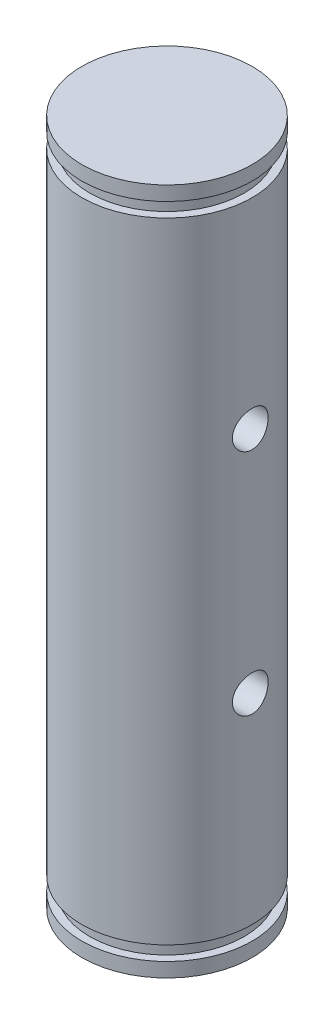
SolidWorks part; units mm, degrees
material "延性铁"
ref_plane "前视基准面" through (0, 0, 0) normal (0, 0, 1) x (1, 0, 0)
ref_plane "上视基准面" through (0, 0, 0) normal (0, 1, 0) x (1, 0, 0)
ref_plane "右视基准面" through (0, 0, 0) normal (1, 0, 0) x (0, 0, -1)
sketch "草图1" plane through (0, 0, 0) normal (0, 1, 0) x (1, 0, 0)
  circle A0 centre (5.9, 0) radius 5.95
  dimension "D1" = 11.9
extrude "凸台-拉伸1" add sketch "草图1" along normal blind 22
sketch "草图2" plane through (0, 22, 0) normal (0, 1, 0) x (1, 0, 0)
  circle A0 centre (5.9, 0) radius 5.4
extrude "凸台-拉伸2" add sketch "草图2" along normal blind 1
sketch "草图3" plane through (0, 23, 0) normal (0, 1, 0) x (1, 0, 0)
  circle A0 centre (5.9, 0) radius 5.95
  dimension "D1" = 11.9
extrude "凸台-拉伸3" add sketch "草图3" along normal blind 1
mirror "镜向10" about plane through (0, 0, 0) normal (0, 1, 0) of "凸台-拉伸3", "凸台-拉伸2", "凸台-拉伸1"
hole_wizard "M3 螺纹孔2" positions "3D草图3" profile "草图6" tap size "M3" standard "GB" end condition through all
sketch3d "3D草图3"
  point P0 (-0.05, -8, 0)
  point P2 (-0.05, 8, 0)
  point P35 (0, 0, 0)
  point P36 (0, 0, 0)
  point P37 (0.0363, -8, -1.0099)
  point P38 (0, 0, 0)
  point P39 (0, 0, 0)
  point P40 (0, 0, 0)
  point P41 (0, 0, 0)
  dimension "D1" = 16
  dimension "D2" = 16
sketch "草图6" plane through (-0.05, -8, 0) normal (0, 1, 0) x (0, 0, 1)
  line L0 (0, 0) -> (0, 11.9)
  line L1 (0, 11.9) -> (1.25, 11.9)
  line L2 (1.25, 11.9) -> (1.25, 0)
  line L5 (1.25, 0) -> (0, 0)
  line L11 (0, -6.35) -> (0, 107.95) construction
  dimension "通孔螺纹孔钻头直径" = 2.5
  dimension "通孔螺纹孔钻头深度" = 11.9
cosmetic thread "孔螺蚊线11" parameters "D2"=3
cosmetic thread "孔螺蚊线12" parameters "D2"=3
